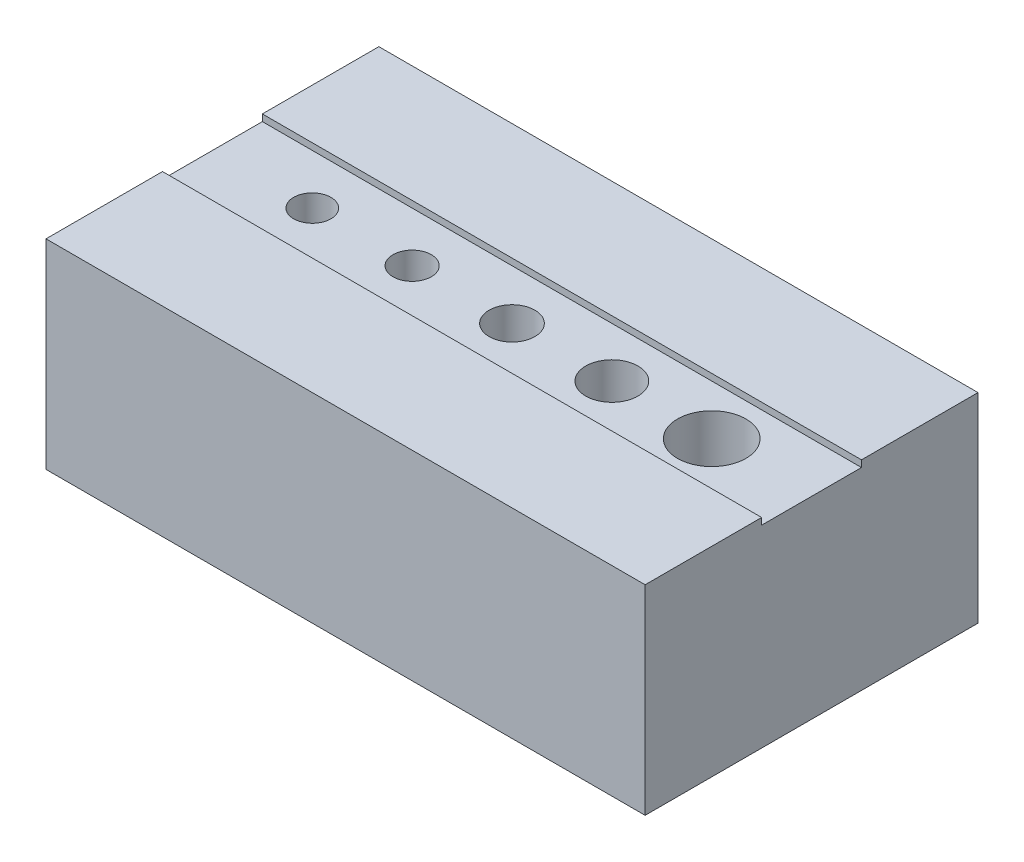
SolidWorks part; units mm, degrees
material "6061-T6 (SS)"
ref_plane "Front Plane" through (0, 0, 0) normal (0, 0, 1) x (1, 0, 0)
ref_plane "Top Plane" through (0, 0, 0) normal (0, 1, 0) x (1, 0, 0)
ref_plane "Right Plane" through (0, 0, 0) normal (1, 0, 0) x (0, 0, -1)
sketch "Sketch1" plane through (0, 0, 0) normal (0, 1, 0) x (1, 0, 0)
  line L1 (-28.575, -15.875) -> (28.575, -15.875)
  line L2 (-28.575, -15.875) -> (-28.575, 15.875)
  line L3 (-28.575, 15.875) -> (28.575, 15.875)
  line L4 (28.575, -15.875) -> (28.575, 15.875)
  line L5 (-28.575, -15.875) -> (28.575, 15.875) construction
  line L6 (-28.575, 15.875) -> (28.575, -15.875) construction
  point P0 (0, 0)
  dimension "D1" = 31.75
  dimension "D2" = 57.15
extrude "Boss-Extrude1" add sketch "Sketch1" along normal blind 19.05
sketch "Sketch2" plane through (0, 19.05, 0) normal (0, 1, 0) x (1, 0, 0)
  line L0 (-28.575, 0) -> (28.575, 0) construction
  line L1 (-28.575, 15.875) -> (-28.575, -15.875) construction
  line L2 (28.575, -15.875) -> (28.575, 15.875) construction
  line L3 (-28.575, 4.7625) -> (28.575, 4.7625)
  line L4 (-28.575, -4.7625) -> (28.575, -4.7625)
  line L5 (28.575, 4.7625) -> (28.575, -4.7625)
  line L6 (-28.575, 4.7625) -> (-28.575, -4.7625)
  dimension "D1" = 9.525
extrude "Cut-Extrude1" cut sketch "Sketch2" against normal blind 0.635
sketch "Sketch3" plane through (0, 18.415, 0) normal (0, 1, 0) x (1, 0, 0)
  line L0 (-28.575, 0) -> (28.575, 0) construction
  line L1 (-28.575, 4.7625) -> (-28.575, -4.7625) construction
  line L2 (28.575, -4.7625) -> (28.575, 4.7625) construction
  circle A0 centre (-19.05, 0) radius 1.778
  circle A1 centre (-9.525, 0) radius 1.8288
  circle A2 centre (0, 0) radius 2.1844
  circle A3 centre (9.525, 0) radius 2.4892
  circle A4 centre (19.05, 0) radius 3.2639
  dimension "D2" = 3.556
  dimension "D4" = 3.6576
  dimension "D6" = 4.3688
  dimension "D8" = 4.9784
  dimension "D10" = 6.5278
  dimension "D1" = 9.525
  dimension "D3" = 19.05
  dimension "D5" = 28.575
  dimension "D7" = 38.1
  dimension "D9" = 47.625
extrude "Cut-Extrude2" cut sketch "Sketch3" against normal through all
